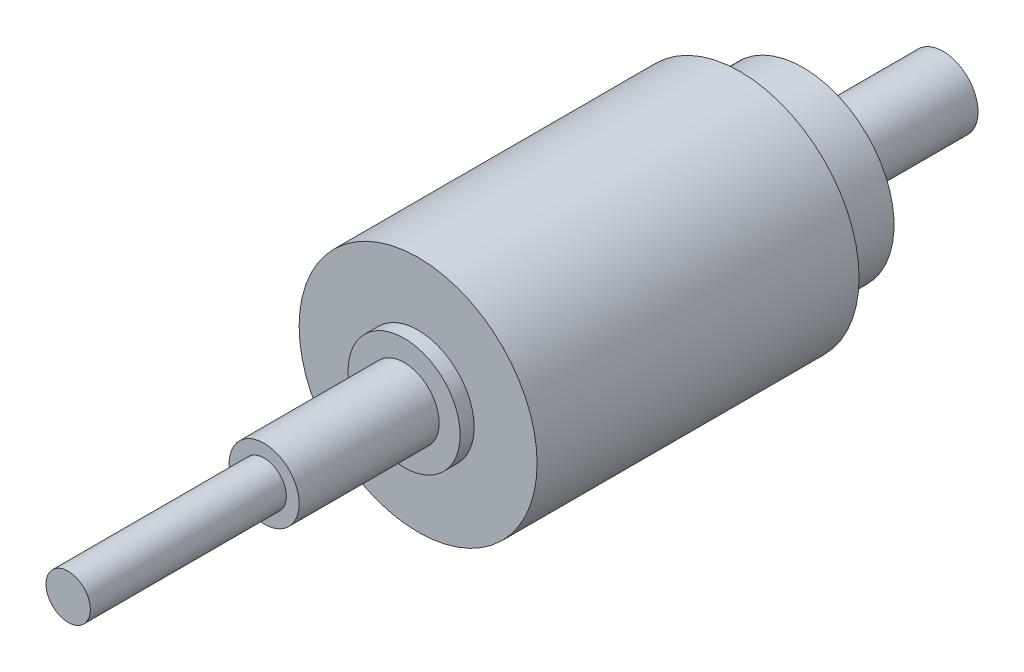
SolidWorks part; units mm, degrees
material "1060 Alloy"
ref_plane "Front Plane" through (0, 0, 0) normal (0, 0, 1) x (1, 0, 0)
ref_plane "Top Plane" through (0, 0, 0) normal (0, 1, 0) x (1, 0, 0)
ref_plane "Right Plane" through (0, 0, 0) normal (1, 0, 0) x (0, 0, -1)
sketch "Sketch1" plane through (0, 0, 0) normal (0, 0, 1) x (1, 0, 0)
  circle A0 centre (0, 0) radius 8.5
  dimension "D1" = 17
extrude "Boss-Extrude1" add sketch "Sketch1" along normal blind 23
sketch "Sketch2" plane through (0, 0, 23) normal (0, 0, 1) x (1, 0, 0)
  circle A0 centre (0, 0) radius 4
extrude "Boss-Extrude2" add sketch "Sketch2" along normal blind 1
sketch "Sketch3" plane through (0, 0, 24) normal (0, 0, 1) x (1, 0, 0)
  circle A0 centre (0, 0) radius 2.5
extrude "Boss-Extrude3" add sketch "Sketch3" along normal blind 10
sketch "Sketch4" plane through (0, 0, 0) normal (0, 0, -1) x (-1, 0, 0)
  circle A0 centre (0, 0) radius 6.5
extrude "Boss-Extrude4" add sketch "Sketch4" along normal blind 4.5
sketch "Sketch5" plane through (0, 0, -4.5) normal (0, 0, -1) x (-1, 0, 0)
  circle A0 centre (0, 0) radius 2.5
extrude "Boss-Extrude5" add sketch "Sketch5" along normal blind 10
sketch "Sketch7" plane through (0, 0, 34) normal (0, 0, 1) x (1, 0, 0)
  circle A0 centre (0, 0) radius 1.585
extrude "Boss-Extrude6" add sketch "Sketch7" along normal blind 14
